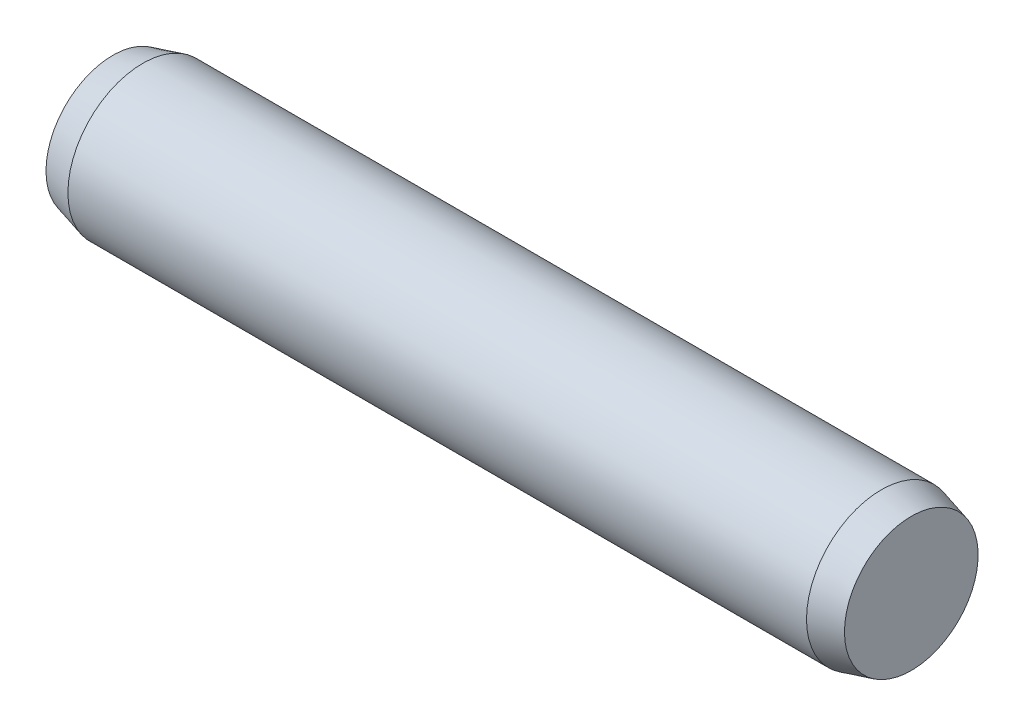
SolidWorks part; units mm, degrees
ref_plane "Plane1" through (0, 0, 0) normal (0, 0, 1) x (1, 0, 0)
ref_plane "Plane2" through (0, 0, 0) normal (0, 1, 0) x (1, 0, 0)
ref_plane "Plane3" through (0, 0, 0) normal (1, 0, 0) x (0, 0, -1)
sketch "Sketch1" plane through (0, 0, 0) normal (0, 0, 1) x (1, 0, 0)
  line L1 (-6.35, 0) -> (107.95, 0) construction
  line L2 (0, 0) -> (32, 0)
  line L3 (32, 0) -> (32, 2.6785)
  line L4 (32, 2.6785) -> (30.8, 3)
  line L5 (30.8, 3) -> (1.2, 3)
  line L6 (0, 2.6785) -> (0, 0)
  line L7 (0, 2.6785) -> (1.2, 3)
  dimension "Chamfer_len" = 1.2
  dimension "D3" = 15
  dimension "Diameter" = 6
  dimension "D1" = 1.2
  dimension "D2" = 15
  dimension "Length" = 32
revolve "Base-Revolve" add sketch "Sketch1" angle 360 about L1
equation "\"D3@Sketch1\" = 15.0"
equation "\"D1@Sketch1\" = \"Chamfer_len@Sketch1\""
equation "\"D2@Sketch1\" = \"D3@Sketch1\""
